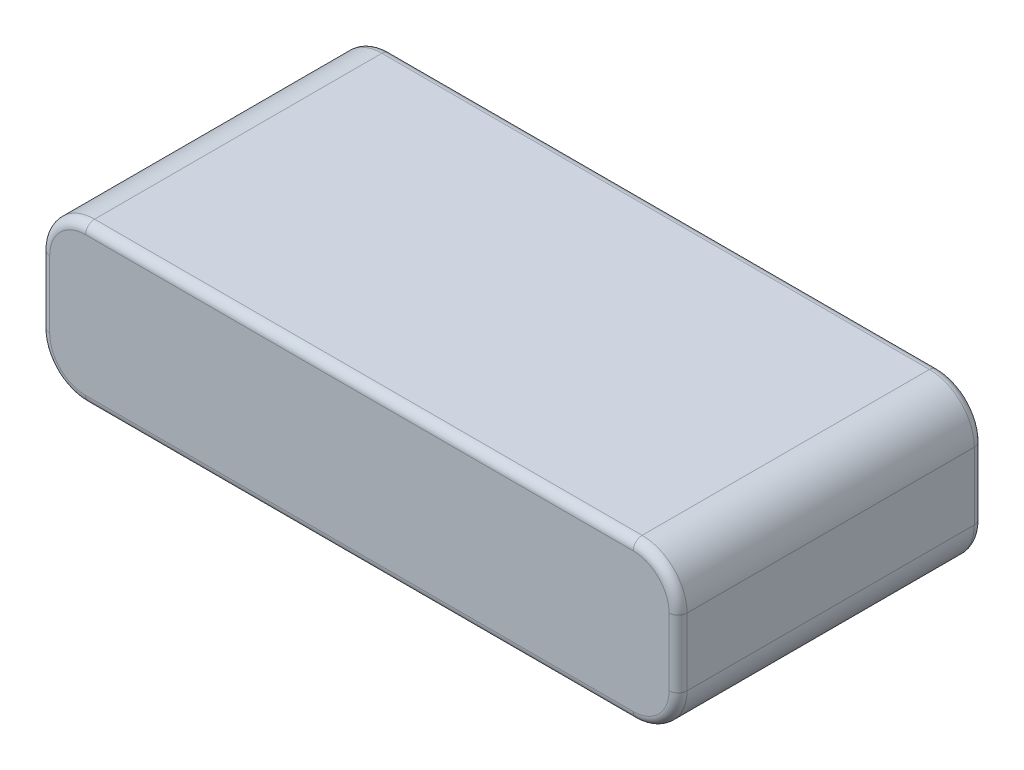
SolidWorks part; units mm, degrees
ref_plane "Front Plane" through (0, 0, 0) normal (0, 0, 1) x (1, 0, 0)
ref_plane "Top Plane" through (0, 0, 0) normal (0, 1, 0) x (1, 0, 0)
ref_plane "Right Plane" through (0, 0, 0) normal (1, 0, 0) x (0, 0, -1)
sketch "Sketch1" plane through (0, 0, 0) normal (0, 1, 0) x (1, 0, 0)
  line L1 (35.5, -17) -> (-35.5, -17)
  line L2 (35.5, -17) -> (35.5, 17)
  line L3 (35.5, 17) -> (-35.5, 17)
  line L4 (-35.5, -17) -> (-35.5, 17)
  line L5 (35.5, -17) -> (-35.5, 17) construction
  line L6 (35.5, 17) -> (-35.5, -17) construction
  point P0 (0, 0)
  dimension "D1" = 71
  dimension "D2" = 34
extrude "Boss-Extrude1" add sketch "Sketch1" along normal blind 17.5
fillet "Fillet1" radius 5 4 edges at (35.5, 0, 0) (35.5, 17.5, 0) (-35.5, 0, 0) (-35.5, 17.5, 0)
fillet "Fillet2" radius 1 16 edges at (34.0355, 16.0355, -17) (0, 17.5, -17) (-34.0355, 16.0355, -17) (-35.5, 8.75, -17) (-34.0355, 1.4645, -17) (0, 0, -17) (34.0355, 1.4645, -17) (35.5, 8.75, -17) (-34.0355, 1.4645, 17) (-35.5, 8.75, 17) (-34.0355, 16.0355, 17) (0, 17.5, 17) (34.0355, 16.0355, 17) (35.5, 8.75, 17) (34.0355, 1.4645, 17) (0, 0, 17)
